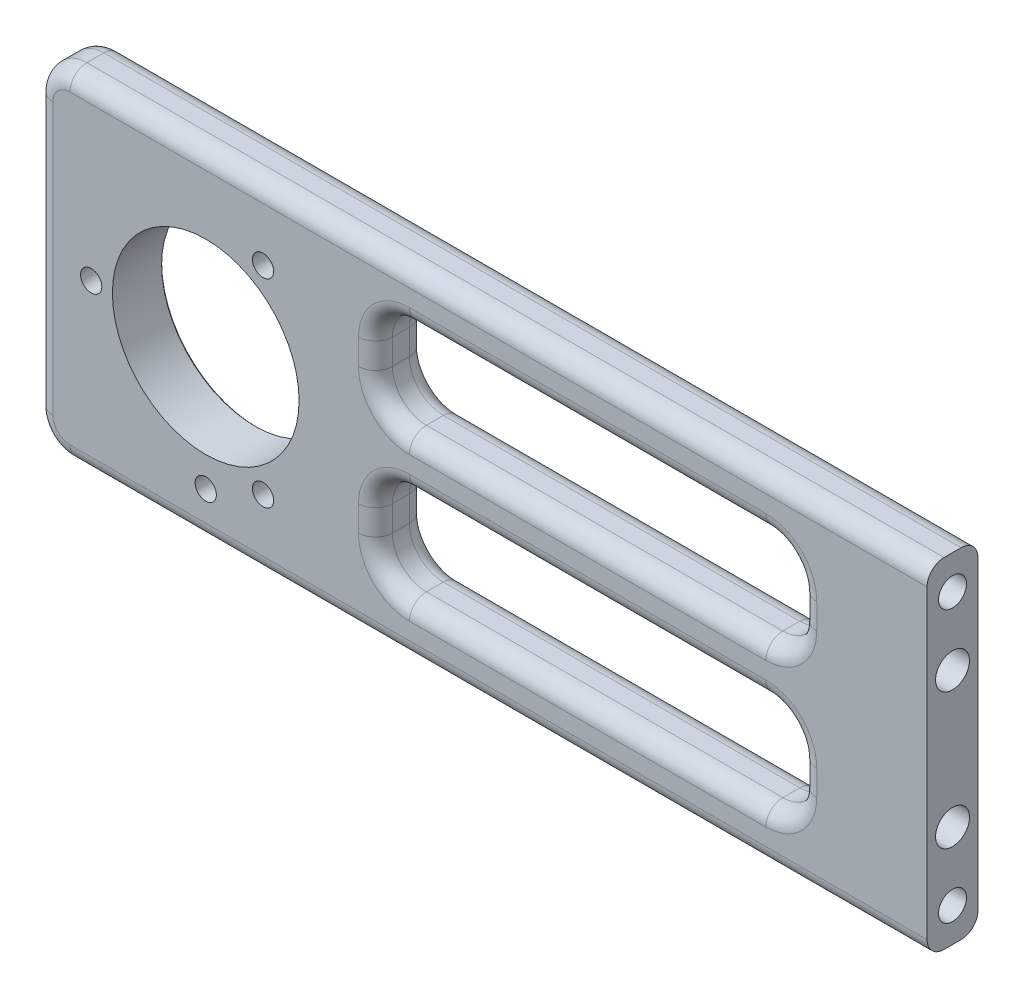
SolidWorks part; units mm, degrees
ref_plane "Face" through (0, 0, 0) normal (0, 0, 1) x (1, 0, 0)
ref_plane "Dessus" through (0, 0, 0) normal (0, 1, 0) x (1, 0, 0)
ref_plane "Droite" through (0, 0, 0) normal (1, 0, 0) x (0, 0, -1)
sketch "Esquisse1" plane through (0, 0, 0) normal (0, 0, 1) x (1, 0, 0)
  line L1 (-16, 20) -> (85, 20)
  line L2 (-20, 16) -> (-20, -16)
  line L3 (-16, -20) -> (85, -20)
  line L4 (85, 20) -> (85, -20)
  arc A0 (-16, -20) -> (-20, -16) centre (-16, -16) cw
  arc A1 (-20, 16) -> (-16, 20) centre (-16, 16) cw
  circle A2 centre (0, 0) radius 11
  point P7 (-20, -20)
  point P10 (-20, 20)
  dimension "D5" = 4
  dimension "D6" = 22
  dimension "D1" = 20
  dimension "D2" = 40
  dimension "D3" = 20
  dimension "D4" = 85
extrude "Boss.-Extru.1" add sketch "Esquisse1" along normal blind 6
sketch "Esquisse16" plane through (0, 0, 0) normal (0, 0, 1) x (1, 0, 0)
  line L0 (20, 8.5) -> (20, -8.5) construction
  line L1 (20, 10) -> (20, 7)
  line L2 (20, 8.5) -> (70, 8.5) construction
  line L3 (70, -7) -> (70, -10)
  line L4 (20, -8.5) -> (70, -8.5) construction
  line L5 (70, 8.5) -> (70, -8.5) construction
  line L6 (24, 3) -> (66, 3)
  line L7 (70, 7) -> (70, 10)
  line L8 (66, 14) -> (24, 14)
  line L9 (20, -7) -> (20, -10)
  line L10 (24, -14) -> (66, -14)
  line L12 (66, -3) -> (24, -3)
  line L14 (85, -20) -> (85, 20) construction
  arc A0 (66, -14) -> (70, -10) centre (66, -10) ccw
  arc A1 (70, 7) -> (66, 3) centre (66, 7) cw
  arc A2 (70, 10) -> (66, 14) centre (66, 10) ccw
  arc A3 (20, 7) -> (24, 3) centre (24, 7) ccw
  arc A4 (20, 10) -> (24, 14) centre (24, 10) cw
  arc A5 (70, -7) -> (66, -3) centre (66, -7) ccw
  arc A7 (20, -10) -> (24, -14) centre (24, -10) ccw
  arc A8 (20, -7) -> (24, -3) centre (24, -7) cw
  point P15 (70, 3)
  point P20 (20, 3)
  point P27 (70, -3)
  point P36 (20, -3)
  dimension "D7" = 4
  dimension "D10" = 4
  dimension "D2" = 20
  dimension "D3" = 8.5
  dimension "D4" = 8.5
  dimension "D5" = 5.5
  dimension "D6" = 5.5
  dimension "D8" = 5.5
  dimension "D9" = 5.5
  dimension "D11" = 15
extrude "Enlèv. mat.-Extru.5" cut sketch "Esquisse16" along normal up to next
fillet "Congé1" radius 2 42 edges at (34.5, 20, 6) (-18.8284, 18.8284, 6) (-20, 0, 6) (-18.8284, -18.8284, 6) (34.5, -20, 6) (34.5, -20, 0) (-18.8284, -18.8284, 0) (-20, 0, 0) (-18.8284, 18.8284, 0) (34.5, 20, 0) (45, -14, 0) (21.1716, -12.8284, 0) (20, -8.5, 0) (21.1716, -4.1716, 0) (68.8284, 12.8284, 0) (70, 8.5, 0) (68.8284, 4.1716, 0) (45, 3, 0) (21.1716, 4.1716, 0) (20, 8.5, 0) (21.1716, 12.8284, 0) (21.1716, -4.1716, 6) (20, -8.5, 6) (21.1716, -12.8284, 6) (45, -14, 6) (68.8284, 4.1716, 6) (70, 8.5, 6) (68.8284, 12.8284, 6) (45, 14, 6) (21.1716, 12.8284, 6) (20, 8.5, 6) (21.1716, 4.1716, 6) (45, -3, 0) (45, 14, 0) (45, -3, 6) (45, 3, 6) (68.8284, -4.1716, 0) (70, -8.5, 0) (68.8284, -12.8284, 0) (68.8284, -12.8284, 6) (70, -8.5, 6) (68.8284, -4.1716, 6)
hole_wizard "Trou taraudé M31" positions "Esquisse19" profile "Esquisse18" tap size "M3" standard "Iso" end condition up to next
sketch "Esquisse19" plane through (0, 0, 0) normal (0, 0, -1) x (-1, 0, 0)
  point P6 (0, -14.5)
  dimension "D3" = 14.5
sketch "Esquisse18" plane through (0, -14.5, 0) normal (1, 0, 0) x (0, 1, 0)
  line L0 (0, 0) -> (0, 6)
  line L1 (0, 6) -> (1.25, 6)
  line L2 (1.25, 6) -> (1.25, 0)
  line L5 (1.25, 0) -> (0, 0)
  line L11 (0, -6.35) -> (0, 107.95) construction
  dimension "Diamètre du trou pour taraudage jusqu'au prochain" = 2.5
  dimension "Profondeur du trou pour taraudage jusqu'au prochain" = 6
cosmetic thread "Filetage de perçage5" parameters "D2"=3
sketch "Esquisse21" plane through (0, 0, 0) normal (0, 0, -1) x (-1, 0, 0)
  line L0 (0, 0) -> (13.5, 0) construction
  line L1 (0, 0) -> (-6.75, 11.6913) construction
  line L2 (0, 0) -> (-6.75, -11.6913) construction
  circle A0 centre (0, 0) radius 13.5 construction
  dimension "D1" = 27
  dimension "D2" = 120
  dimension "D3" = 120
hole_wizard "Trou taraudé M33" positions "Esquisse25" profile "Esquisse24" tap size "M3" standard "Iso" end condition up to next
sketch "Esquisse25" plane through (0, 0, 0) normal (0, 0, -1) x (-1, 0, 0)
  point P3 (-6.75, 11.6913)
  point P6 (-6.75, -11.6913)
  point P10 (13.5, 0)
sketch "Esquisse24" plane through (6.75, 11.6913, 0) normal (1, 0, 0) x (0, 1, 0)
  line L0 (0, 0) -> (0, 6)
  line L1 (0, 6) -> (1.25, 6)
  line L2 (1.25, 6) -> (1.25, 0)
  line L5 (1.25, 0) -> (0, 0)
  line L11 (0, -6.35) -> (0, 107.95) construction
  dimension "Diamètre du trou pour taraudage jusqu'au prochain" = 2.5
  dimension "Profondeur du trou pour taraudage jusqu'au prochain" = 6
cosmetic thread "Filetage de perçage9" parameters "D2"=3
cosmetic thread "Filetage de perçage10" parameters "D2"=3
cosmetic thread "Filetage de perçage11" parameters "D2"=3
chamfer "Chanfrein1" distance 0.2 angle 45 1 edges at (11, 0, 0)
hole_wizard "Diamètre du perçage Ø4.0 (4)1" positions "Esquisse27" profile "Esquisse26" hole size "Ø4.0" standard "Ansi Metric"
sketch "Esquisse27" plane through (85, 0, 0) normal (1, 0, 0) x (0, 0, -1)
  line L0 (0, 0) -> (0, 11.6913) construction
  line L1 (0, -13.5) -> (0, 13.5) construction
  point P0 (-3, 8)
  point P2 (-3, -8)
  dimension "D1" = 3
  dimension "D2" = 3
  dimension "D3" = 8
  dimension "D4" = 8
sketch "Esquisse26" plane through (85, 8, 3) normal (0, 1, 0) x (0, 0, -1)
  line L0 (0, 0) -> (0, 6.2017)
  line L1 (0, 6.2017) -> (2, 5)
  line L2 (2, 5) -> (2, 0)
  line L5 (2, 0) -> (0, 0)
  line L10 (0, 6.2017) -> (-2, 5) construction
  line L11 (0, -6.35) -> (0, 107.95) construction
  dimension "Diamètre du perçage" = 4
  dimension "Profondeur du perçage" = 5
  dimension "Angle de pointe" = 118
hole_wizard "Trou taraudé M41" positions "Esquisse29" profile "Esquisse28" tap size "M4" standard "Iso"
sketch "Esquisse29" plane through (85, 0, 0) normal (1, 0, 0) x (0, 0, -1)
  point P0 (-3, 16)
  point P2 (-3, -16)
  dimension "D1" = 16
  dimension "D2" = 16
  dimension "D3" = 3
  dimension "D4" = 3
sketch "Esquisse28" plane through (85, 16, 3) normal (0, 1, 0) x (0, 0, -1)
  line L0 (0, 0) -> (0, 12.4914)
  line L1 (0, 12.4914) -> (1.65, 11.5)
  line L2 (1.65, 11.5) -> (1.65, 0)
  line L5 (1.65, 0) -> (0, 0)
  line L10 (0, 12.4914) -> (-1.65, 11.5) construction
  line L11 (0, -6.35) -> (0, 107.95) construction
  dimension "Diamètre du trou pour taraudage" = 3.3
  dimension "Profondeur du trou pour taraudage" = 11.5
  dimension "Angle de pointe" = 118
cosmetic thread "Filetage de perçage12" parameters "D1"=8, "D2"=4
cosmetic thread "Filetage de perçage13" parameters "D1"=8, "D2"=4
